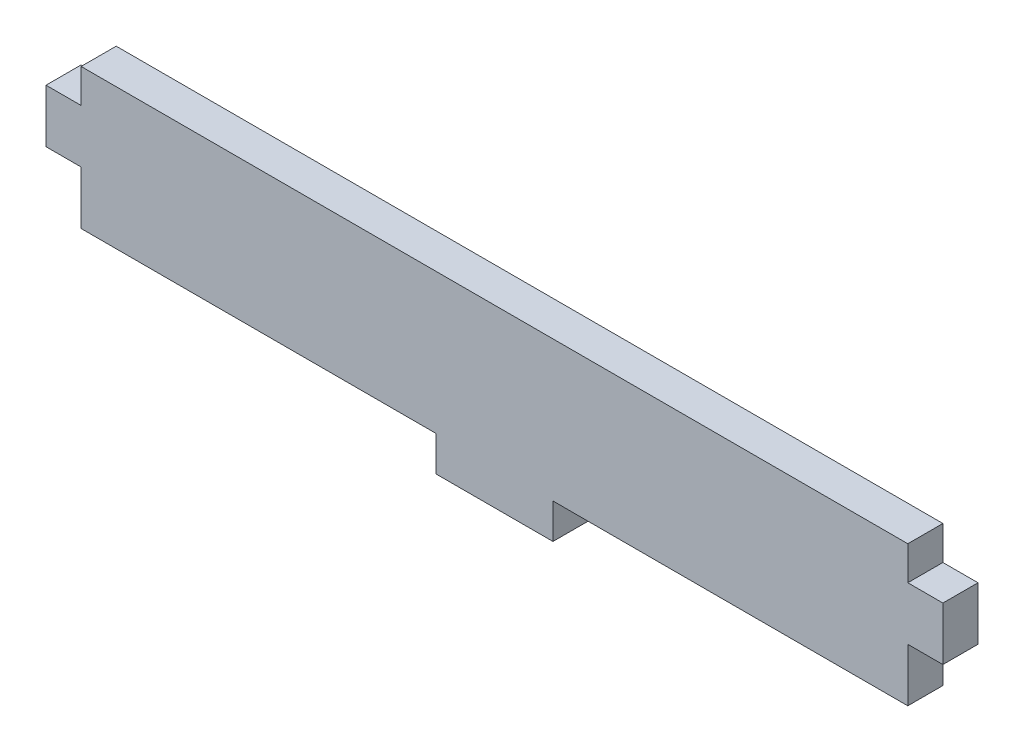
SolidWorks part; units mm, degrees
ref_plane "Front Plane" through (0, 0, 0) normal (0, 0, 1) x (1, 0, 0)
ref_plane "Top Plane" through (0, 0, 0) normal (0, 1, 0) x (1, 0, 0)
ref_plane "Right Plane" through (0, 0, 0) normal (1, 0, 0) x (0, 0, -1)
sketch "Sketch1" plane through (0, 0, 0) normal (0, 0, 1) x (1, 0, 0)
  line L0 (115, 45) -> (115, 0) construction
  line L1 (0, 0) -> (230, 0)
  line L2 (0, 0) -> (0, 45)
  line L3 (0, 45) -> (230, 45)
  line L4 (230, 0) -> (230, 45)
  line L5 (100, 4.5) -> (115, 4.5) construction
  line L6 (0, 9) -> (230, 9)
  line L7 (0, 9) -> (0, 0)
  line L8 (0, 0) -> (230, 0)
  line L9 (230, 9) -> (230, 0)
  line L10 (115, 4.5) -> (130, 4.5) construction
  line L11 (100, 9) -> (130, 9)
  line L12 (100, 9) -> (100, 0)
  line L13 (100, 0) -> (130, 0)
  line L14 (130, 9) -> (130, 0)
  line L15 (221, 36.3333) -> (221, 22.6667)
  line L16 (0, 36.3333) -> (9, 36.3333)
  line L17 (0, 36.3333) -> (0, 22.6667)
  line L18 (0, 22.6667) -> (9, 22.6667)
  line L19 (9, 36.3333) -> (9, 22.6667)
  line L20 (230, 22.6667) -> (221, 22.6667)
  line L21 (230, 36.3333) -> (230, 22.6667)
  line L22 (230, 36.3333) -> (221, 36.3333)
  line L23 (9, 45) -> (9, 9)
  line L24 (221, 9) -> (221, 45)
  dimension "D1" = 230
  dimension "45" = 45
  dimension "D3" = 9
  dimension "D4" = 30
  dimension "D5" = 9
  dimension "D6" = 13.6667
  dimension "D7" = 22.6667
extrude "Boss-Extrude1" add sketch "Sketch1" along normal blind 9 contours L6 L24 L15 L3 L23 L19 | L19 L16 L2 L18 | L14 L6 L12 L8 | L4 L22 L15 L20
equation "\"D6@Sketch1\"=41/3"
equation "\"D7@Sketch1\"=41/3+9"
